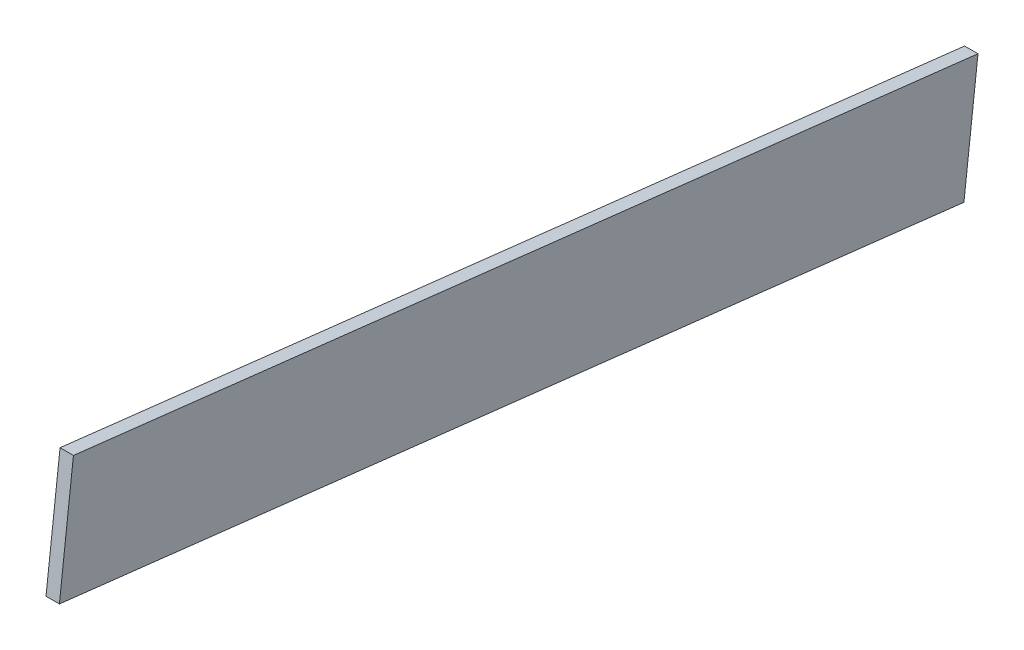
SolidWorks part; units mm, degrees
material "Acrylic (Medium-high impact)"
ref_plane "Front Plane" through (0, 0, 0) normal (0, 0, 1) x (1, 0, 0)
ref_plane "Top Plane" through (0, 0, 0) normal (0, 1, 0) x (1, 0, 0)
ref_plane "Right Plane" through (0, 0, 0) normal (1, 0, 0) x (0, 0, -1)
sketch "Sketch1" plane through (-223, 0, 0) normal (-1, 0, 0) x (0, 0, 1)
  line L4 (-293.7836, 362.8255) -> (-291.163, 340.1208)
  line L5 (-291.163, 340.1208) -> (-122.2842, 359.6131)
  line L6 (-122.2842, 359.6131) -> (-124.9048, 382.3177)
  line L7 (-124.9048, 382.3177) -> (-293.7836, 362.8255)
  line L8 (-293.7836, 362.8255) -> (-291.163, 340.1208)
  line L9 (-291.163, 340.1208) -> (-122.2842, 359.6131)
  line L10 (-122.2842, 359.6131) -> (-124.9048, 382.3177)
  line L11 (-124.9048, 382.3177) -> (-293.7836, 362.8255)
  dimension "D1" = 0
extrude "Boss-Extrude1" add sketch "Sketch1" along normal up to vertex (2.5 mm away)
